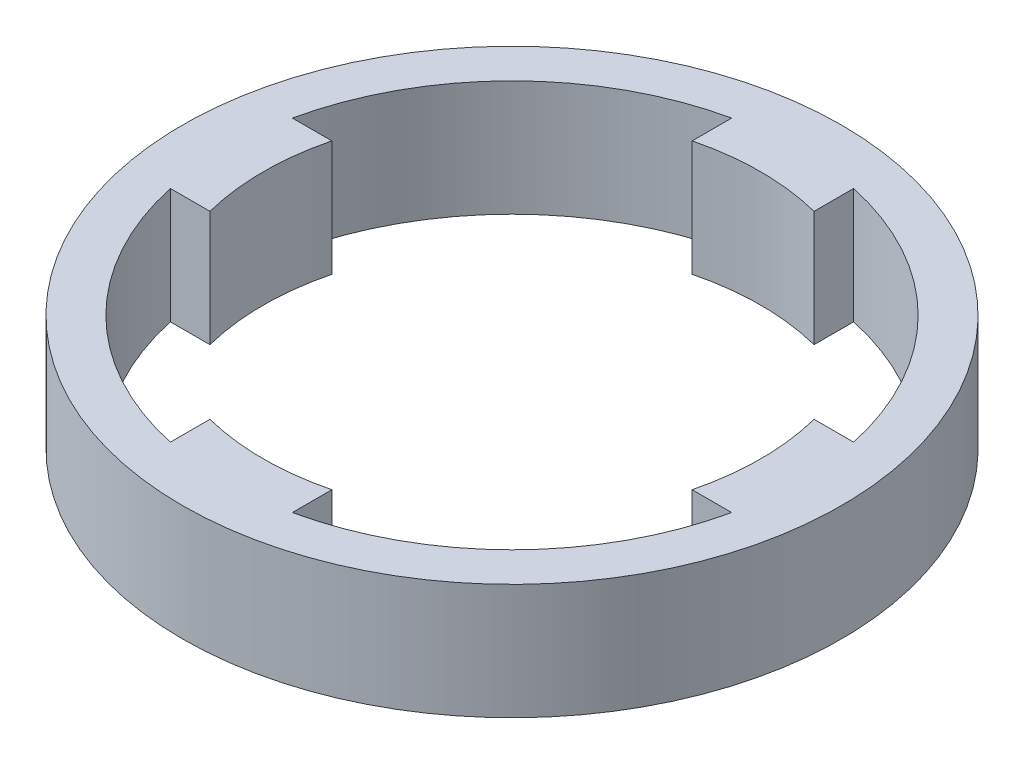
SolidWorks part; units mm, degrees
material "Резина"
ref_plane "Спереди" through (0, 0, 0) normal (0, 0, 1) x (1, 0, 0)
ref_plane "Сверху" through (0, 0, 0) normal (0, 1, 0) x (1, 0, 0)
ref_plane "Справа" through (0, 0, 0) normal (1, 0, 0) x (0, 0, -1)
sketch "Эскиз1" plane through (0, 0, 0) normal (0, 1, 0) x (1, 0, 0)
  line L8 (-4.75, 21.865) -> (-4.75, 18.7837)
  line L9 (4.75, 21.865) -> (4.75, 18.7837)
  line L10 (18.7837, 4.75) -> (21.865, 4.75)
  line L11 (21.865, -4.75) -> (18.7837, -4.75)
  line L12 (4.75, -18.7837) -> (4.75, -21.865)
  line L13 (-4.75, -21.865) -> (-4.75, -18.7837)
  line L14 (-18.7837, -4.75) -> (-21.865, -4.75)
  line L15 (-21.865, 4.75) -> (-18.7837, 4.75)
  arc A9 (4.75, 18.7837) -> (-4.75, 18.7837) centre (0, 0) ccw
  arc A10 (21.865, 4.75) -> (4.75, 21.865) centre (0, 0) ccw
  arc A11 (18.7837, -4.75) -> (18.7837, 4.75) centre (0, 0) ccw
  arc A12 (4.75, -21.865) -> (21.865, -4.75) centre (0, 0) ccw
  arc A13 (-4.75, -18.7837) -> (4.75, -18.7837) centre (0, 0) ccw
  arc A14 (-21.865, -4.75) -> (-4.75, -21.865) centre (0, 0) ccw
  arc A15 (-18.7837, 4.75) -> (-18.7837, -4.75) centre (0, 0) ccw
  arc A16 (-4.75, 21.865) -> (-21.865, 4.75) centre (0, 0) ccw
  circle A17 centre (0, 0) radius 25.675
extrude "Бобышка-Вытянуть1" add sketch "Эскиз1" along normal blind 9
